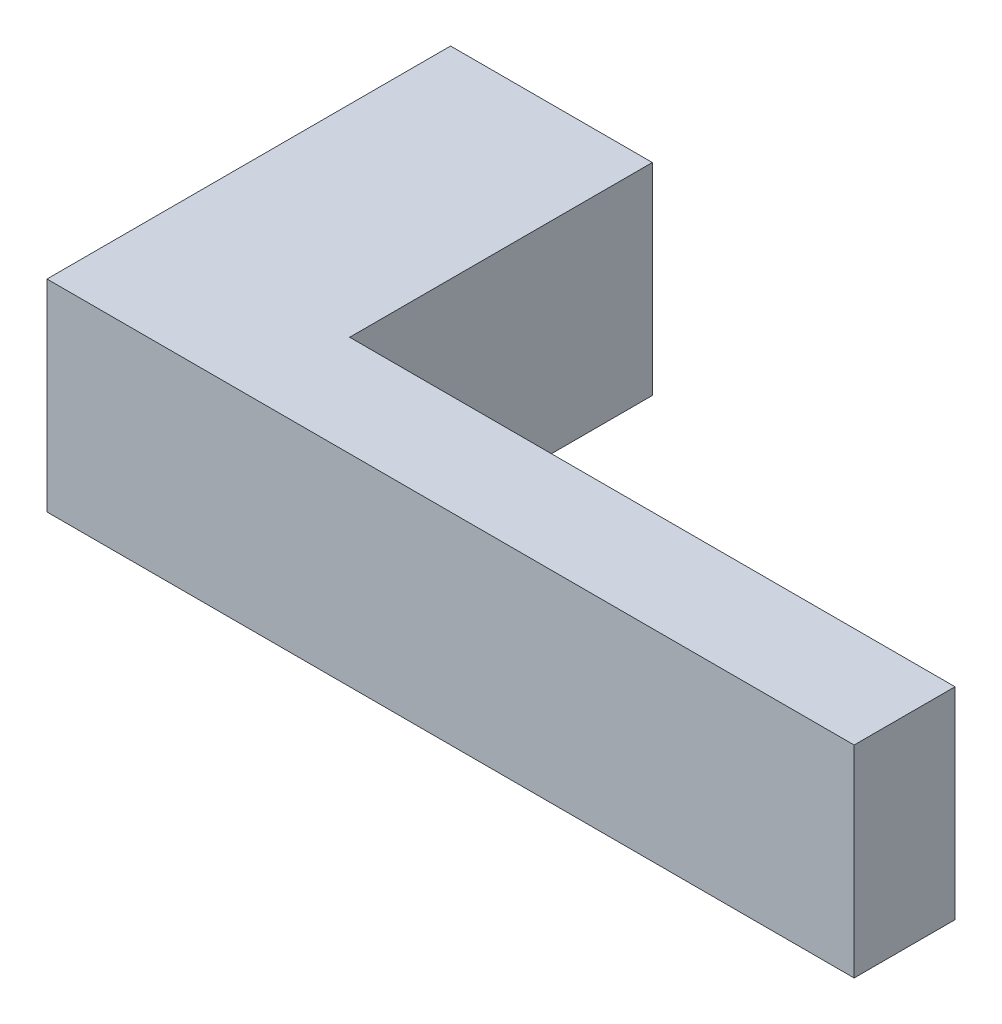
SolidWorks part; units mm, degrees
ref_plane "Přední rovina" through (0, 0, 0) normal (0, 0, 1) x (1, 0, 0)
ref_plane "Horní rovina" through (0, 0, 0) normal (0, 1, 0) x (1, 0, 0)
ref_plane "Pravá rovina" through (0, 0, 0) normal (1, 0, 0) x (0, 0, -1)
sketch "Sketch2" plane through (0, 0, 0) normal (0, 1, 0) x (1, 0, 0)
  line L0 (0, -40) -> (0, 0)
  line L1 (80, -40) -> (0, -40)
  line L2 (80, -40) -> (80, -30)
  line L3 (80, -30) -> (20, -30)
  line L7 (0, 0) -> (20, 0)
  line L8 (20, -30) -> (20, 0)
  dimension "D1" = 80
  dimension "D2" = 10
  dimension "D3" = 30
  dimension "D4" = 20
extrude "Boss-Extrude1" add sketch "Sketch2" along normal blind 20
